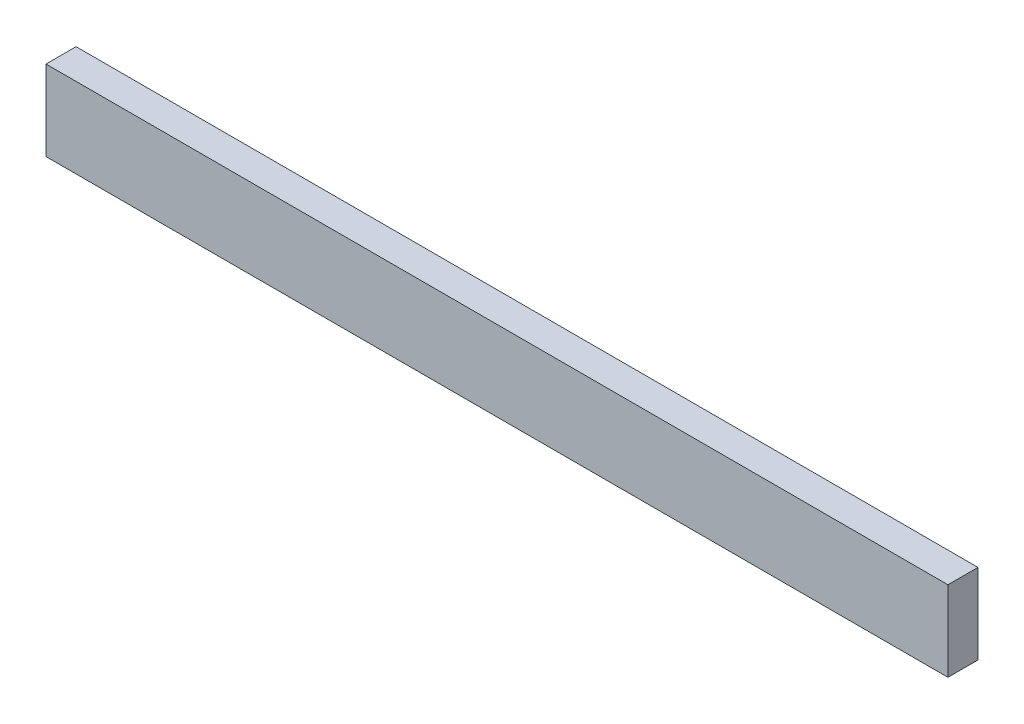
SolidWorks part; units mm, degrees
material "PTFE (geral)"
ref_plane "Plano frontal" through (0, 0, 0) normal (0, 0, 1) x (1, 0, 0)
ref_plane "Plano superior" through (0, 0, 0) normal (0, 1, 0) x (1, 0, 0)
ref_plane "Plano direito" through (0, 0, 0) normal (1, 0, 0) x (0, 0, -1)
sketch "Esboço1" plane through (0, 0, 0) normal (0, 0, 1) x (1, 0, 0)
  line L1 (-45, -4) -> (45, -4)
  line L2 (-45, -4) -> (-45, 4)
  line L3 (-45, 4) -> (45, 4)
  line L4 (45, -4) -> (45, 4)
  line L5 (-45, -4) -> (45, 4) construction
  line L6 (-45, 4) -> (45, -4) construction
  point P0 (0, 0)
  dimension "D1" = 90
  dimension "D2" = 8
extrude "Ressalto-extrusão1" add sketch "Esboço1" along normal blind 3
